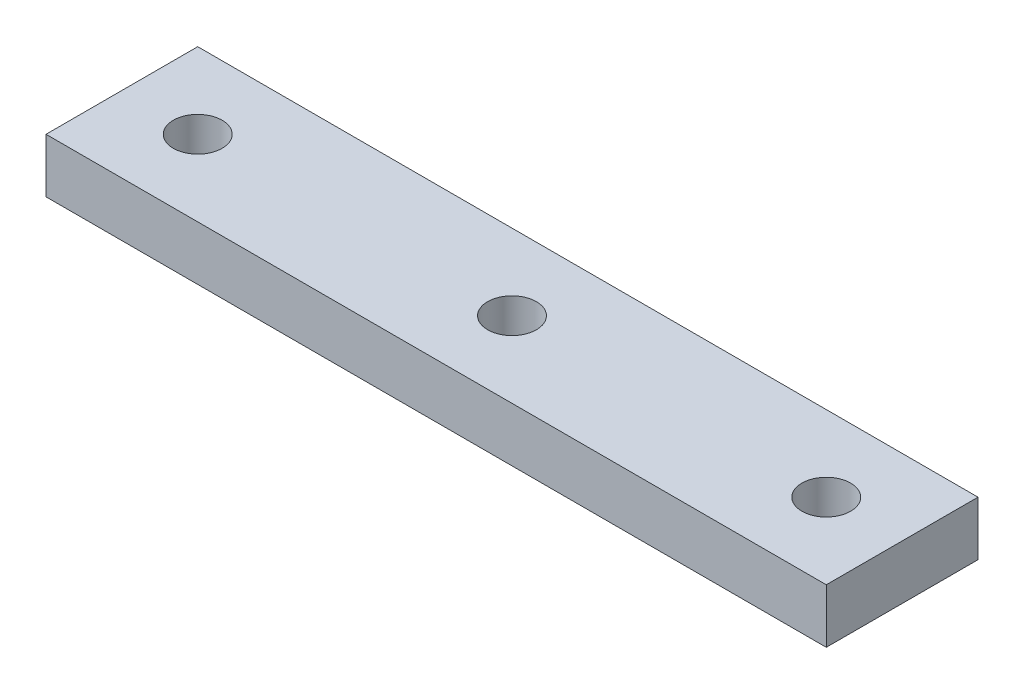
SolidWorks part; units mm, degrees
material "Acrylic (Medium-high impact)"
ref_plane "Front Plane" through (0, 0, 0) normal (0, 0, 1) x (1, 0, 0)
ref_plane "Top Plane" through (0, 0, 0) normal (0, 1, 0) x (1, 0, 0)
ref_plane "Right Plane" through (0, 0, 0) normal (1, 0, 0) x (0, 0, -1)
sketch "Sketch1" plane through (0, 0, 0) normal (0, 1, 0) x (1, 0, 0)
  line L1 (-36, 7) -> (36, 7)
  line L2 (-36, 7) -> (-36, -7)
  line L3 (-36, -7) -> (36, -7)
  line L4 (36, 7) -> (36, -7)
  line L5 (-36, 7) -> (36, -7) construction
  line L6 (-36, -7) -> (36, 7) construction
  circle A0 centre (0, 0) radius 2.25
  circle A1 centre (29, 0) radius 2.25
  circle A2 centre (-29, 0) radius 2.25
  point P0 (0, 0)
  dimension "D3" = 4.5
  dimension "D4" = 4.5
  dimension "D5" = 4.5
  dimension "D1" = 14
  dimension "D2" = 72
extrude "Boss-Extrude1" add sketch "Sketch1" along normal blind 5
